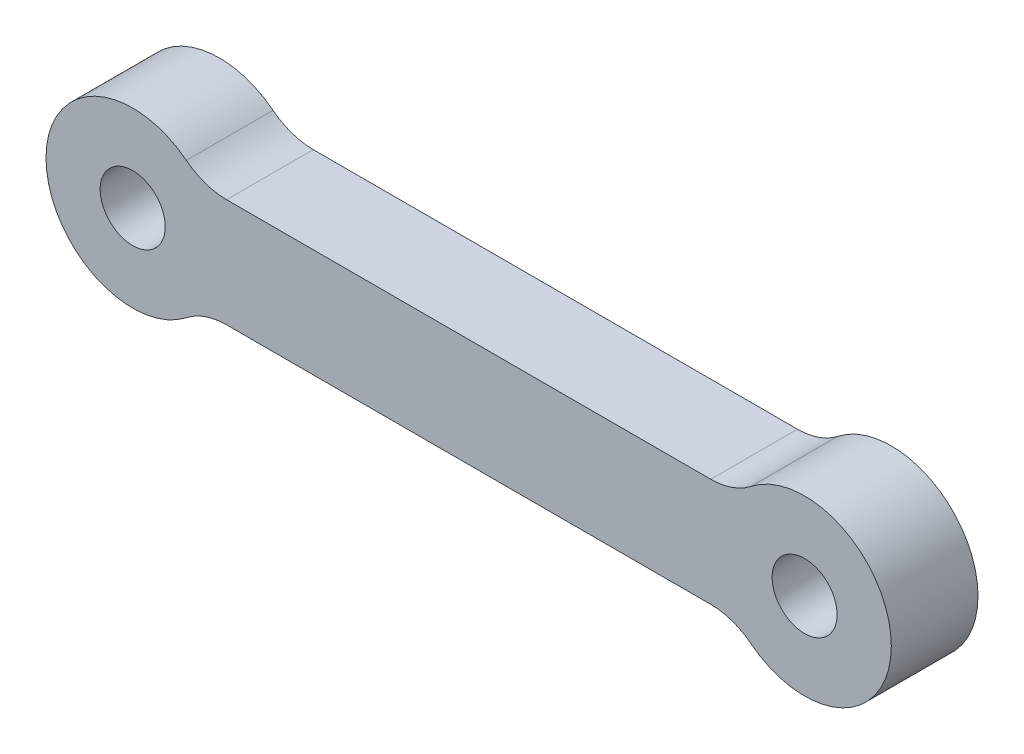
SolidWorks part; units mm, degrees
ref_plane "Front Plane" through (0, 0, 0) normal (0, 0, 1) x (1, 0, 0)
ref_plane "Top Plane" through (0, 0, 0) normal (0, 1, 0) x (1, 0, 0)
ref_plane "Right Plane" through (0, 0, 0) normal (1, 0, 0) x (0, 0, -1)
sketch "Sketch1" plane through (0, 0, 0) normal (0, 0, 1) x (1, 0, 0)
  line L0 (-15.5, 0) -> (15.5, 0) construction
  line L1 (0, 0) -> (0, 5.4598) construction
  line L3 (11.1699, -2.5) -> (-11.1699, -2.5)
  line L5 (11.1699, 2.5) -> (-11.1699, 2.5)
  line L7 (12.3775, -2.5) -> (-12.3775, 2.5) construction
  line L8 (12.3775, 2.5) -> (-12.3775, -2.5) construction
  circle A0 centre (-15.5, 0) radius 1.5
  arc A1 (-13.0256, 3.1429) -> (-13.0256, -3.1429) centre (-15.5, 0) ccw
  arc A2 (13.0256, 3.1429) -> (13.0256, -3.1429) centre (15.5, 0) cw
  circle A3 centre (15.5, 0) radius 1.5
  arc A4 (11.1699, -2.5) -> (13.0256, -3.1429) centre (11.1699, -5.5) cw
  arc A5 (13.0256, 3.1429) -> (11.1699, 2.5) centre (11.1699, 5.5) cw
  arc A6 (-11.1699, -2.5) -> (-13.0256, -3.1429) centre (-11.1699, -5.5) ccw
  arc A7 (-11.1699, 2.5) -> (-13.0256, 3.1429) centre (-11.1699, 5.5) cw
  point P4 (0, 0)
  dimension "D2" = 8
  dimension "D3" = 3
  dimension "D5" = 3
  dimension "D1" = 31
  dimension "D4" = 5
extrude "Boss-Extrude1" add sketch "Sketch1" along normal blind 4
